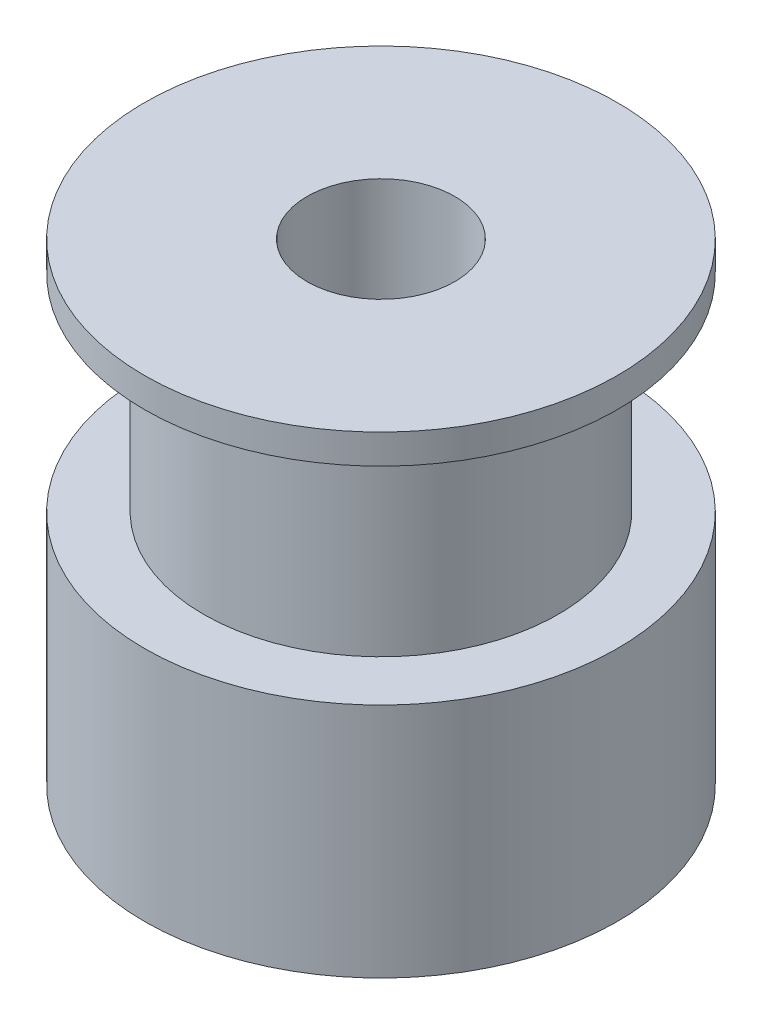
SolidWorks part; units mm, degrees
material "合金钢"
ref_plane "前视基准面" through (0, 0, 0) normal (0, 0, 1) x (1, 0, 0)
ref_plane "上视基准面" through (0, 0, 0) normal (0, 1, 0) x (1, 0, 0)
ref_plane "右视基准面" through (0, 0, 0) normal (1, 0, 0) x (0, 0, -1)
sketch "草图1" plane through (0, 0, 0) normal (0, 1, 0) x (1, 0, 0)
  circle A0 centre (0, 0) radius 8
  circle A1 centre (0, 0) radius 2.5
extrude "凸台-拉伸1" add sketch "草图1" along normal blind 8
sketch "草图2" plane through (0, 8, 0) normal (0, 1, 0) x (1, 0, 0)
  circle A1 centre (0, 0) radius 6
  circle A3 centre (0, 0) radius 2.5 construction
  circle A4 centre (0, 0) radius 2.5
extrude "凸台-拉伸2" add sketch "草图2" along normal blind 7
sketch "草图3" plane through (0, 15, 0) normal (0, 1, 0) x (1, 0, 0)
  circle A0 centre (0, 0) radius 2.5
  circle A1 centre (0, 0) radius 8
extrude "凸台-拉伸3" add sketch "草图3" along normal blind 1
